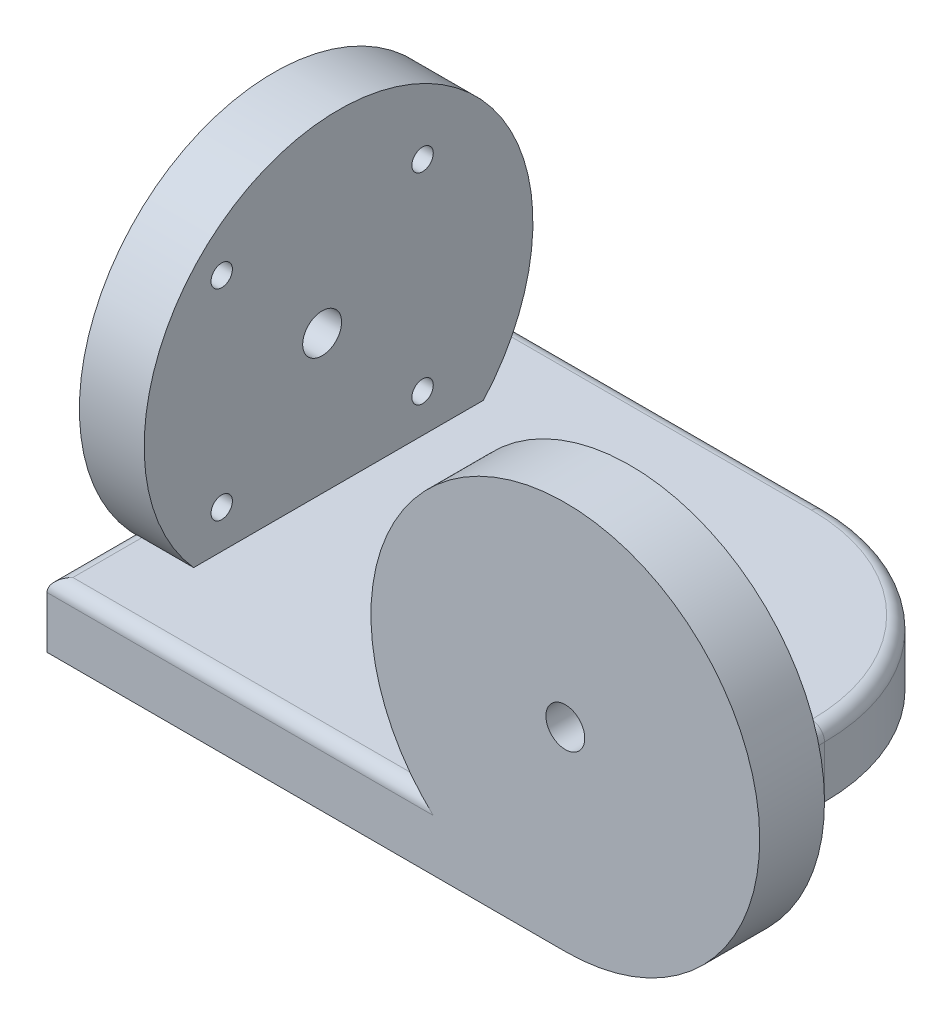
SolidWorks part; units mm, degrees
ref_plane "Front Plane" through (0, 0, 0) normal (0, 0, 1) x (1, 0, 0)
ref_plane "Top Plane" through (0, 0, 0) normal (0, 1, 0) x (1, 0, 0)
ref_plane "Right Plane" through (0, 0, 0) normal (1, 0, 0) x (0, 0, -1)
sketch "Sketch1" plane through (0, 0, 0) normal (0, 0, 1) x (1, 0, 0)
  circle A0 centre (0, 0) radius 30
  dimension "D1" = 60
extrude "Boss-Extrude1" add sketch "Sketch1" along normal blind 10
sketch "Sketch2" plane through (0, 0, 10) normal (0, 0, 1) x (1, 0, 0)
  line L1 (0, -30) -> (-80, -30)
  line L2 (0, -30) -> (0, -20)
  line L3 (0, -20) -> (-80, -20)
  line L4 (-80, -30) -> (-80, -20)
  circle A0 centre (0, 0) radius 30 construction
  dimension "D1" = 10
  dimension "D2" = 80
extrude "Boss-Extrude2" add sketch "Sketch2" against normal blind 70
sketch "Sketch3" plane through (-80, 0, 0) normal (-1, 0, 0) x (0, 0, 1)
  line L0 (-60, -30) -> (10, -30) construction
  line L1 (-60, -20) -> (10, -20) construction
  circle A0 centre (-25, 0) radius 30
  point P7 (-25, -20)
  dimension "D1" = 60
extrude "Boss-Extrude3" add sketch "Sketch3" against normal blind 10
hole_wizard "Ø6.0mm Dowel Hole2" positions "Sketch8" profile "Sketch9" hole size "Ø6.0" standard "ANSI Metric" end condition through all
sketch "Sketch8" plane through (0, 0, 0) normal (0, 0, -1) x (-1, 0, 0)
  point P0 (0, 0)
sketch "Sketch9" plane through (0, 0, 0) normal (1, 0, 0) x (0, 1, 0)
  line L0 (0, 0) -> (0, 10)
  line L1 (0, 10) -> (3, 10)
  line L2 (3, 10) -> (3, 0)
  line L5 (3, 0) -> (0, 0)
  line L11 (0, -6.35) -> (0, 107.95) construction
  dimension "Thru Hole Dia." = 6
  dimension "Thru Hole Depth" = 10
hole_wizard "M4x0.7 Tapped Hole2" positions "Sketch10" profile "Sketch11" tap size "M4x0.7" standard "ANSI Metric"
sketch "Sketch10" plane through (0, 0, 0) normal (0, 0, -1) x (-1, 0, 0)
  point P0 (-15.5, 15.5)
  point P2 (15.5, 15.5)
  point P4 (15.5, -15.5)
  point P6 (-15.5, -15.5)
  dimension "D1" = 31
  dimension "D2" = 31
  dimension "D3" = 15.5
  dimension "D4" = 15.5
sketch "Sketch11" plane through (15.5, 15.5, 0) normal (1, 0, 0) x (0, 1, 0)
  line L0 (0, 0) -> (0, 6.9914)
  line L1 (0, 6.9914) -> (1.65, 6)
  line L2 (1.65, 6) -> (1.65, 0)
  line L5 (1.65, 0) -> (0, 0)
  line L10 (0, 6.9914) -> (-1.65, 6) construction
  line L11 (0, -6.35) -> (0, 107.95) construction
  dimension "Tap Drill Dia." = 3.3
  dimension "Tap Drill Depth" = 6
  dimension "Drill Angle" = 118
cosmetic thread "Hole Thread5" parameters "D1"=5, "D2"=4
cosmetic thread "Hole Thread6" parameters "D1"=5, "D2"=4
cosmetic thread "Hole Thread7" parameters "D1"=5, "D2"=4
cosmetic thread "Hole Thread8" parameters "D1"=5, "D2"=4
hole_wizard "Ø6.0mm Dowel Hole4" positions "Sketch19" profile "Sketch21" hole size "Ø6.0" standard "ANSI Metric" end condition through all
sketch "Sketch19" plane through (-70, 1.4071, -22.469) normal (1, 0, 0) x (0, 0, -1)
  point P0 (0, 0)
sketch "Sketch21" plane through (-70, 1.4071, -22.469) normal (0, 1, 0) x (0, 0, -1)
  line L0 (0, 0) -> (0, 10)
  line L1 (0, 10) -> (3, 10)
  line L2 (3, 10) -> (3, 0)
  line L5 (3, 0) -> (0, 0)
  line L11 (0, -6.35) -> (0, 107.95) construction
  dimension "Thru Hole Dia." = 6
  dimension "Thru Hole Depth" = 10
hole_wizard "M4x0.7 Tapped Hole4" positions "Sketch23" profile "Sketch25" tap size "M4x0.7" standard "ANSI Metric"
sketch "Sketch23" plane through (-70, 1.4071, -22.469) normal (1, 0, 0) x (0, 0, -1)
  circle A0 centre (0, 0) radius 3 construction
  point P0 (-15.5, 15.5)
  point P2 (15.5, 15.5)
  point P4 (15.5, -15.5)
  point P6 (-15.5, -15.5)
  dimension "D1" = 31
  dimension "D2" = 31
  dimension "D3" = 15.5
  dimension "D4" = 15.5
sketch "Sketch25" plane through (-70, 16.9071, -6.969) normal (0, 1, 0) x (0, 0, -1)
  line L0 (0, 0) -> (0, 6.9914)
  line L1 (0, 6.9914) -> (1.65, 6)
  line L2 (1.65, 6) -> (1.65, 0)
  line L5 (1.65, 0) -> (0, 0)
  line L10 (0, 6.9914) -> (-1.65, 6) construction
  line L11 (0, -6.35) -> (0, 107.95) construction
  dimension "Tap Drill Dia." = 3.3
  dimension "Tap Drill Depth" = 6
  dimension "Drill Angle" = 118
cosmetic thread "Hole Thread13" parameters "D1"=5, "D2"=4
cosmetic thread "Hole Thread14" parameters "D1"=5, "D2"=4
cosmetic thread "Hole Thread15" parameters "D1"=5, "D2"=4
cosmetic thread "Hole Thread16" parameters "D1"=5, "D2"=4
fillet "Fillet1" radius 30 1 edges at (0, -25, -60)
fillet "Fillet2" radius 2 6 edges at (-51.1803, -20, 10) (-80, -20, -53.6803) (-80, -20, 3.6803) (-55, -20, -60) (-8.7868, -20, -51.2132) (0, -20, -15)
